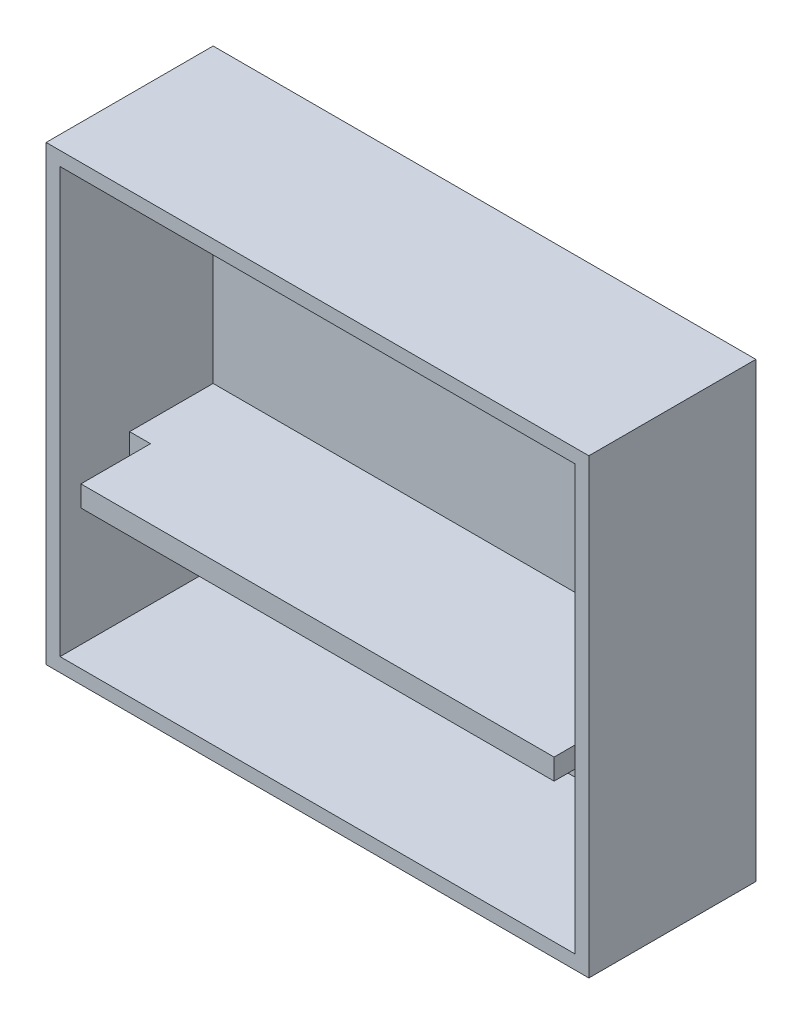
SolidWorks part; units mm, degrees
ref_plane "Front Plane" through (0, 0, 0) normal (0, 0, 1) x (1, 0, 0)
ref_plane "Top Plane" through (0, 0, 0) normal (0, 1, 0) x (1, 0, 0)
ref_plane "Right Plane" through (0, 0, 0) normal (1, 0, 0) x (0, 0, -1)
sketch "Sketch1" plane through (0, 0, 0) normal (0, 0, 1) x (1, 0, 0)
  line L1 (0, 0) -> (78, 0)
  line L2 (0, 0) -> (0, 65)
  line L3 (0, 65) -> (78, 65)
  line L4 (78, 0) -> (78, 65)
  dimension "D1" = 65
  dimension "D2" = 78
extrude "Boss-Extrude1" add sketch "Sketch1" along normal blind 24
sketch "Sketch2" plane through (0, 0, 24) normal (0, 0, 1) x (1, 0, 0)
  line L0 (78, 65) -> (0, 65) construction
  line L1 (2, 63) -> (76, 63)
  line L2 (2, 63) -> (2, 2)
  line L3 (2, 2) -> (76, 2)
  line L4 (76, 63) -> (76, 2)
  line L5 (0, 65) -> (0, 0) construction
  line L6 (78, 0) -> (78, 65) construction
  line L7 (0, 0) -> (78, 0) construction
  dimension "D1" = 2
  dimension "D2" = 2
  dimension "D3" = 2
  dimension "D4" = 2
extrude "Cut-Extrude1" cut sketch "Sketch2" against normal blind 22
sketch "Sketch3" plane through (0, 0, 2) normal (0, 0, 1) x (1, 0, 0)
  line L0 (2, 63) -> (2, 2) construction
  line L1 (2, 25) -> (76, 25)
  line L2 (2, 25) -> (2, 22)
  line L3 (2, 22) -> (76, 22)
  line L4 (76, 25) -> (76, 22)
  line L5 (76, 2) -> (76, 63) construction
  line L6 (2, 2) -> (76, 2) construction
  dimension "D1" = 3
  dimension "D2" = 20
extrude "Boss-Extrude2" add sketch "Sketch3" along normal blind 22
sketch "Sketch4" plane through (0, 0, 24) normal (0, 0, 1) x (1, 0, 0)
  line L0 (2, 22) -> (76, 22) construction
  line L1 (2, 25) -> (5, 25)
  line L2 (2, 25) -> (2, 22)
  line L3 (2, 22) -> (5, 22)
  line L4 (5, 25) -> (5, 22)
  line L5 (2, 22) -> (76, 22) construction
  line L6 (76, 25) -> (73, 25)
  line L7 (76, 25) -> (76, 22)
  line L8 (76, 22) -> (73, 22)
  line L9 (73, 25) -> (73, 22)
  dimension "D1" = 3
  dimension "D2" = 3
extrude "Cut-Extrude2" cut sketch "Sketch4" against normal blind 10
sketch "Sketch5" plane through (0, 0, 2) normal (0, 0, 1) x (1, 0, 0)
  line L0 (76, 63) -> (2, 63) construction
  line L1 (76, 25) -> (76, 63) construction
  circle A0 centre (20.5, 56) radius 2.5
  circle A1 centre (69, 56) radius 2.5
  dimension "D1" = 5
  dimension "D2" = 5
  dimension "D3" = 7
  dimension "D4" = 7
  dimension "D5" = 7
  dimension "D6" = 48.5
extrude "Boss-Extrude3" add sketch "Sketch5" along normal blind 3
sketch "Sketch6" plane through (0, 0, 5) normal (0, 0, 1) x (1, 0, 0)
  circle A0 centre (20.5, 56) radius 1
  circle A1 centre (69, 56) radius 1
  dimension "D1" = 2
  dimension "D2" = 2
extrude "Boss-Extrude4" add sketch "Sketch6" along normal blind 5
